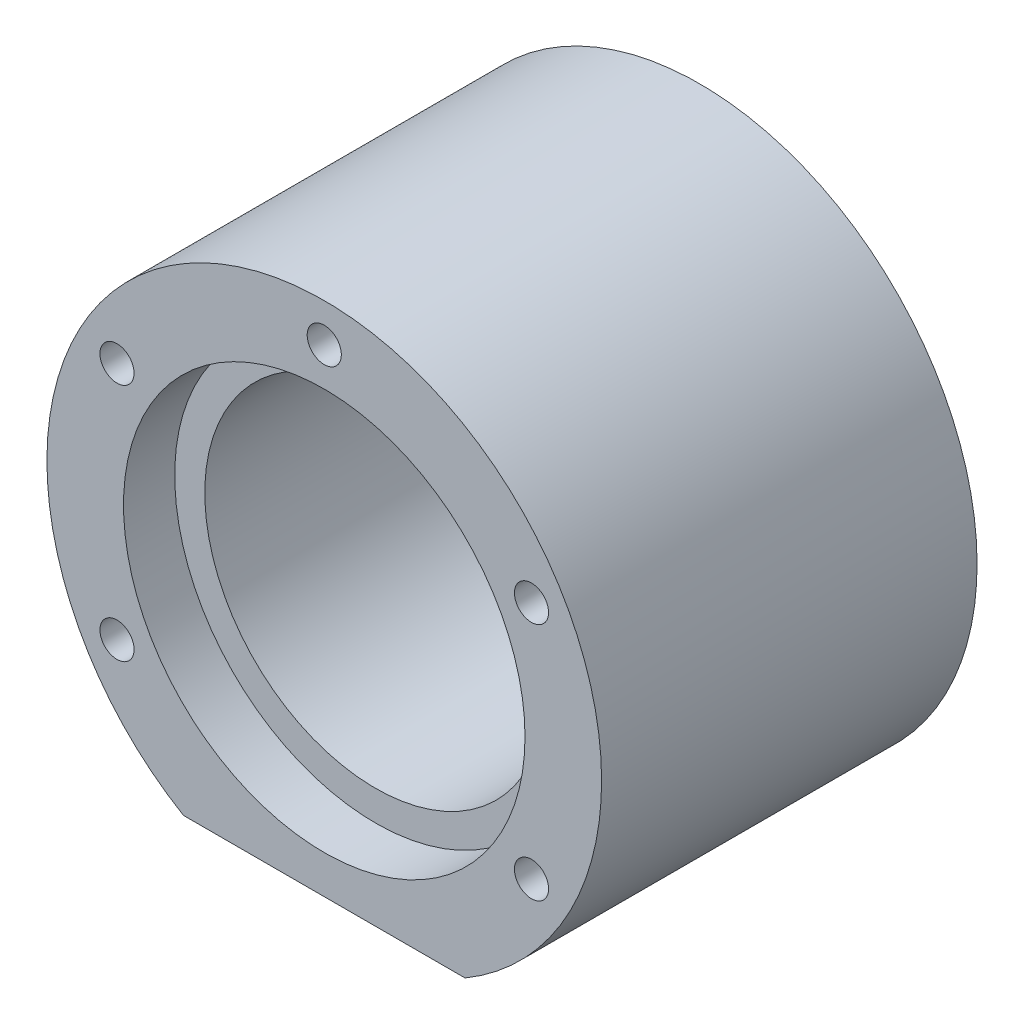
SolidWorks part; units mm, degrees
ref_plane "Front Plane" through (0, 0, 0) normal (0, 0, 1) x (1, 0, 0)
ref_plane "Top Plane" through (0, 0, 0) normal (0, 1, 0) x (1, 0, 0)
ref_plane "Right Plane" through (0, 0, 0) normal (1, 0, 0) x (0, 0, -1)
sketch "Sketch1" plane through (0, 0, 0) normal (0, 0, 1) x (1, 0, 0)
  line L0 (-16.5, -28) -> (16.5, -28)
  circle A0 centre (0, 0) radius 23.525
  arc A1 (16.5, -28) -> (-16.5, -28) centre (0, 0) ccw
  circle A2 centre (0, 28) radius 2
  circle A3 centre (24.2861, 13.9784) radius 2
  circle A4 centre (24.2861, -14.0647) radius 2
  circle A6 centre (-24.2861, -14.0647) radius 2
  circle A7 centre (-24.2861, 13.9784) radius 2
  arc A8 (1.233, -26.5116) -> (-1.233, -26.5116) centre (0, -28.0863) ccw [skipped]
  point P19 (0, -0.0431)
  dimension "D1" = 47.05
  dimension "D2" = 65
  dimension "D6" = 4
  dimension "D3" = 28
  dimension "D5" = 28
  dimension "D4" = 6
extrude "Boss-Extrude1" add sketch "Sketch1" along normal blind 44
ref_plane "Plane1" through (0, 0, 22) normal (0, 0, 1) x (1, 0, 0)
sketch "Sketch2" plane through (0, 0, 22) normal (0, 0, 1) x (1, 0, 0)
  circle A0 centre (0, 0) radius 23.6
  circle A1 centre (0, 0) radius 20
  dimension "D1" = 40
extrude "Boss-Extrude2" add sketch "Sketch2" along normal blind 16 and the other way blind 16
thread "Thread1" [suppressed] pitch 0.7 start angle 0, offset 0, length 0, pitch 0.7, diameter 4
ref_plane "Plane2" through (-2, 28, 35) normal (0, -1, 0) x (-1, 0, 0)
sketch "Thread Profile1" plane through (-2, 28, 35) normal (0, -1, 0) x (-1, 0, 0)
  line L0 (0, 0) -> (0, 0.7) construction
  line L11 (0, 0) -> (0, 0.6125)
  line L12 (0, 0.6125) -> (-0.3789, 0.3937)
  line L13 (-0.3789, 0.3937) -> (-0.3789, 0.2187)
  line L15 (-0.3789, 0.2187) -> (0, 0)
  line L17 (-0.3789, 0.3062) -> (0, 0.3062) construction
  point P2 (0, 0)
  dimension "Pitch" = 0.7
  dimension "Profile_Angle" = 60
  dimension "Profile_Land" = 0.175
  dimension "Profile_Height" = 0.3789
thread "Thread2" [suppressed] pitch 0.7 start angle 0, offset 0, length 0, pitch 0.7, diameter 4
ref_plane "Plane3" through (22.2861, 13.9784, 35) normal (0, -1, 0) x (-1, 0, 0)
sketch "Thread Profile2" plane through (22.2861, 13.9784, 35) normal (0, -1, 0) x (-1, 0, 0)
  line L0 (0, 0) -> (0, 0.7) construction
  line L11 (0, 0) -> (0, 0.6125)
  line L12 (0, 0.6125) -> (-0.3789, 0.3937)
  line L13 (-0.3789, 0.3937) -> (-0.3789, 0.2187)
  line L15 (-0.3789, 0.2187) -> (0, 0)
  line L17 (-0.3789, 0.3062) -> (0, 0.3062) construction
  point P2 (0, 0)
  dimension "Pitch" = 0.7
  dimension "Profile_Angle" = 60
  dimension "Profile_Land" = 0.175
  dimension "Profile_Height" = 0.3789
thread "Thread3" [suppressed] pitch 0.7 start angle 0, offset 0, length 0, pitch 0.7, diameter 4
ref_plane "Plane4" through (22.2861, -14.0647, 35) normal (0, -1, 0) x (-1, 0, 0)
sketch "Thread Profile3" plane through (22.2861, -14.0647, 35) normal (0, -1, 0) x (-1, 0, 0)
  line L0 (0, 0) -> (0, 0.7) construction
  line L11 (0, 0) -> (0, 0.6125)
  line L12 (0, 0.6125) -> (-0.3789, 0.3937)
  line L13 (-0.3789, 0.3937) -> (-0.3789, 0.2187)
  line L15 (-0.3789, 0.2187) -> (0, 0)
  line L17 (-0.3789, 0.3062) -> (0, 0.3062) construction
  point P2 (0, 0)
  dimension "Pitch" = 0.7
  dimension "Profile_Angle" = 60
  dimension "Profile_Land" = 0.175
  dimension "Profile_Height" = 0.3789
thread "Thread4" [suppressed] pitch 0.7 start angle 0, offset 0, length 0, pitch 0.7, diameter 4
ref_plane "Plane5" through (-26.2861, 13.9784, 35) normal (0, -1, 0) x (-1, 0, 0)
sketch "Thread Profile4" [suppressed] plane through (-26.2861, 13.9784, 35) normal (0, -1, 0) x (-1, 0, 0)
  line L0 (0, 0) -> (0, 0.7) construction
  line L11 (0, 0) -> (0, 0.6125)
  line L12 (0, 0.6125) -> (-0.3789, 0.3937)
  line L13 (-0.3789, 0.3937) -> (-0.3789, 0.2187)
  line L15 (-0.3789, 0.2187) -> (0, 0)
  line L17 (-0.3789, 0.3062) -> (0, 0.3062) construction
  point P2 (0, 0)
  dimension "Pitch" = 0.7
  dimension "Profile_Angle" = 60
  dimension "Profile_Land" = 0.175
  dimension "Profile_Height" = 0.3789
thread "Thread5" [suppressed] pitch 0.7 start angle 0, offset 0, length 0, pitch 0.7, diameter 4
ref_plane "Plane6" through (-26.2861, -14.0647, 35) normal (0, -1, 0) x (-1, 0, 0)
sketch "Thread Profile5" plane through (-26.2861, -14.0647, 35) normal (0, -1, 0) x (-1, 0, 0)
  line L0 (0, 0) -> (0, 0.7) construction
  line L11 (0, 0) -> (0, 0.6125)
  line L12 (0, 0.6125) -> (-0.3789, 0.3937)
  line L13 (-0.3789, 0.3937) -> (-0.3789, 0.2187)
  line L15 (-0.3789, 0.2187) -> (0, 0)
  line L17 (-0.3789, 0.3062) -> (0, 0.3062) construction
  point P2 (0, 0)
  dimension "Pitch" = 0.7
  dimension "Profile_Angle" = 60
  dimension "Profile_Land" = 0.175
  dimension "Profile_Height" = 0.3789
